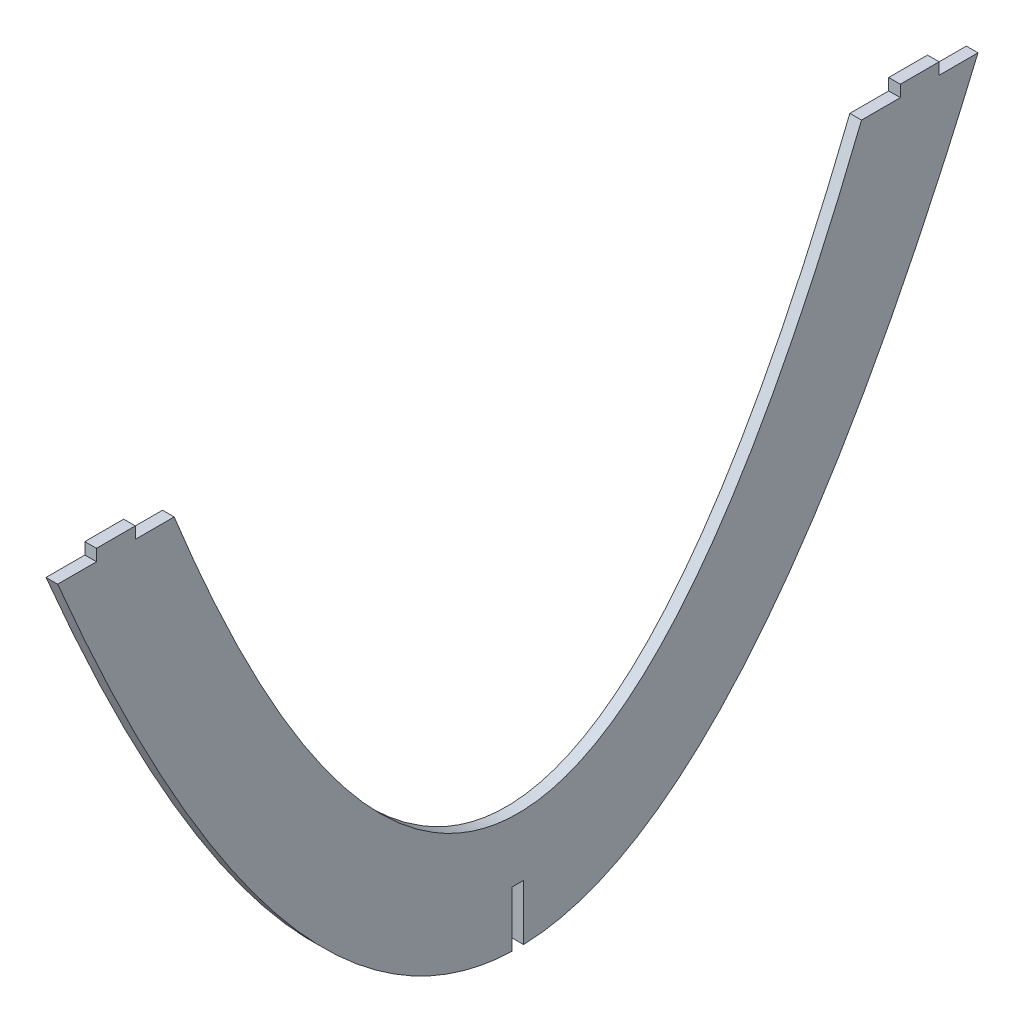
SolidWorks part; units mm, degrees
ref_plane "前视基准面" through (0, 0, 0) normal (0, 0, 1) x (1, 0, 0)
ref_plane "上视基准面" through (0, 0, 0) normal (0, 1, 0) x (1, 0, 0)
ref_plane "右视基准面" through (0, 0, 0) normal (1, 0, 0) x (0, 0, -1)
sketch "草图1" plane through (0, 0, 0) normal (1, 0, 0) x (0, 0, -1)
  line L0 (-118.4911, 150.0012) -> (-88.4915, 150.0012)
  line L1 (88.4915, 150.0012) -> (118.4911, 150.0012)
  spline S0 degree 2 poles (-132.7478, 185.8197) (0, -166.62) (132.7478, 185.8197) knots 0 0 0 1 1 1 construction
  spline S1 degree 2 poles (-118.4911, 150.0012) (0, -130.8015) (118.4911, 150.0012) knots 0.053699 0.053699 0.053699 0.946301 0.946301 0.946301
  spline S2 degree 2 poles (-131.651, 283.9538) (0, -204.7541) (131.651, 283.9538) knots 0 0 0 1 1 1 construction
  spline S3 degree 2 poles (-88.4915, 150.0012) (0, -70.8015) (88.4915, 150.0012) knots 0.163916 0.163916 0.163916 0.836084 0.836084 0.836084
extrude "凸台-拉伸1" add sketch "草图1" along normal blind 3
sketch "草图2" plane through (0, 150.0012, 0) normal (0, 1, 0) x (1, 0, 0)
  line L0 (0, -118.4911) -> (3, -88.4915)
  line L1 (0, 88.4915) -> (3, 118.4911)
  line L2 (0, 118.4911) -> (0, 88.4915) construction
  line L3 (3, 98.4913) -> (0, 98.4913)
  line L4 (3, 98.4913) -> (3, 108.4913)
  line L5 (3, 108.4913) -> (0, 108.4913)
  line L6 (0, 98.4913) -> (0, 108.4913)
  line L7 (3, 98.4913) -> (0, 108.4913) construction
  line L8 (3, 108.4913) -> (0, 98.4913) construction
  line L9 (0, -88.4915) -> (0, -118.4911) construction
  line L10 (3, -108.4913) -> (0, -108.4913)
  line L11 (3, -108.4913) -> (3, -98.4913)
  line L12 (3, -98.4913) -> (0, -98.4913)
  line L13 (0, -108.4913) -> (0, -98.4913)
  line L14 (3, -108.4913) -> (0, -98.4913) construction
  line L15 (3, -98.4913) -> (0, -108.4913) construction
  point P8 (1.5, 103.4913)
  point P15 (1.5, -103.4913)
  line M1 (0, -88.4915) -> (0, -118.4911)
  line M3 (3, -118.4911) -> (3, -88.4915)
extrude "凸台-拉伸2" add sketch "草图2" along normal blind 3 contours L6 L3 L1 L5 | L4 L5 L1 L3 | L12 L0 L10 M3 | L0 L12 L10 M1
sketch "草图3" plane through (0, 0, 0) normal (-1, 0, 0) x (0, 0, 1)
  line L0 (-1.5, 39.9999) -> (-1.5, 23.9677) construction
  line L1 (-1.5, 39.9999) -> (-1.5, 23.9677)
  line L2 (1.5, 39.9999) -> (1.5, 23.9677) construction
  line L3 (1.5, 39.9999) -> (1.5, 23.9677)
  line L5 (-1.5, 23.9677) -> (1.5, 23.9677)
  line L6 (-1.5, 23.9677) -> (-1.5, 2.1624)
  line L7 (-1.5, 2.1624) -> (1.5, 2.1624)
  line L8 (1.5, 23.9677) -> (1.5, 2.1624)
  spline M7 degree 2 poles (-118.4911, 150.0012) (0, -130.8015) (118.4911, 150.0012) knots 0.053699 0.053699 0.053699 0.946301 0.946301 0.946301
extrude "切除-拉伸1" cut sketch "草图3" against normal through all contours L8 L5 L6 M7
